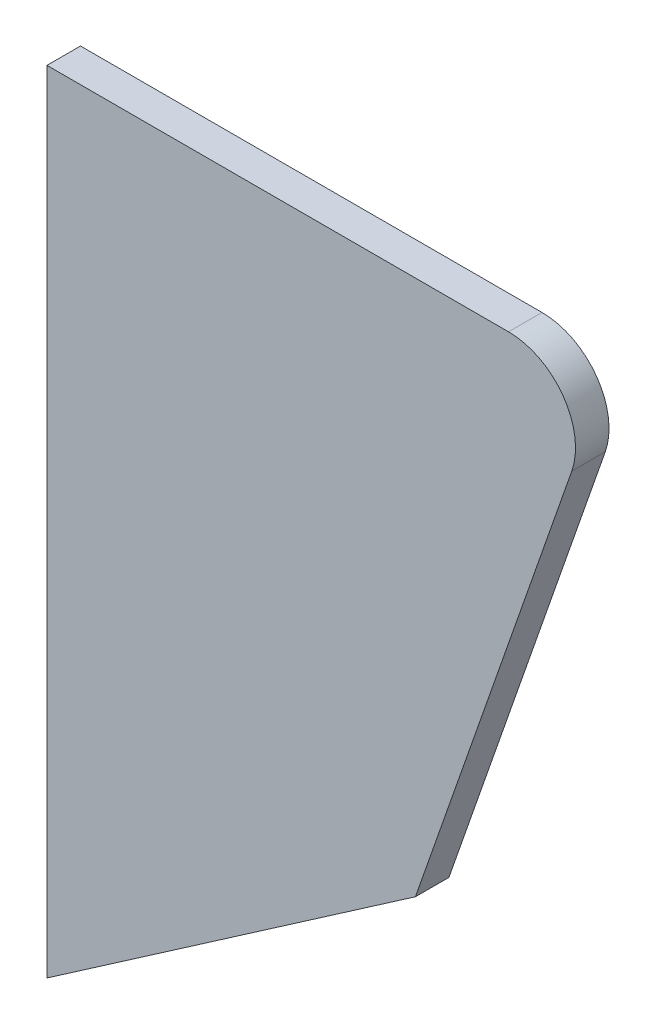
SolidWorks part; units mm, degrees
material "POM Acetal Copolymer"
ref_plane "Front" through (0, 0, 0) normal (0, 0, 1) x (1, 0, 0)
ref_plane "Top" through (0, 0, 0) normal (0, 1, 0) x (1, 0, 0)
ref_plane "Right" through (0, 0, 0) normal (1, 0, 0) x (0, 0, -1)
sketch "Sketch1" plane through (0, 0, 0) normal (0, 0, 1) x (1, 0, 0)
  line L0 (-41.5, -38) -> (-41.5, 80)
  line L1 (-41.5, 80) -> (27.4052, 80)
  line L2 (36.8438, 66.6965) -> (13.5, 0)
  line L3 (13.5, 0) -> (-41.5, -38)
  line L4 (0, 118.8975) -> (0, -147.1175) construction
  arc A0 (27.4052, 80) -> (36.8438, 66.6965) centre (27.4052, 70) cw
  point P4 (13.5, 0)
  point P8 (-41.5, -42.5375)
  point P11 (41.5, 80)
  dimension "D5" = 10
  dimension "D1" = 83
  dimension "D2" = 80
  dimension "D3" = 55
  dimension "D4" = 118
extrude "Boss-Extrude1" add sketch "Sketch1" along normal blind 5
